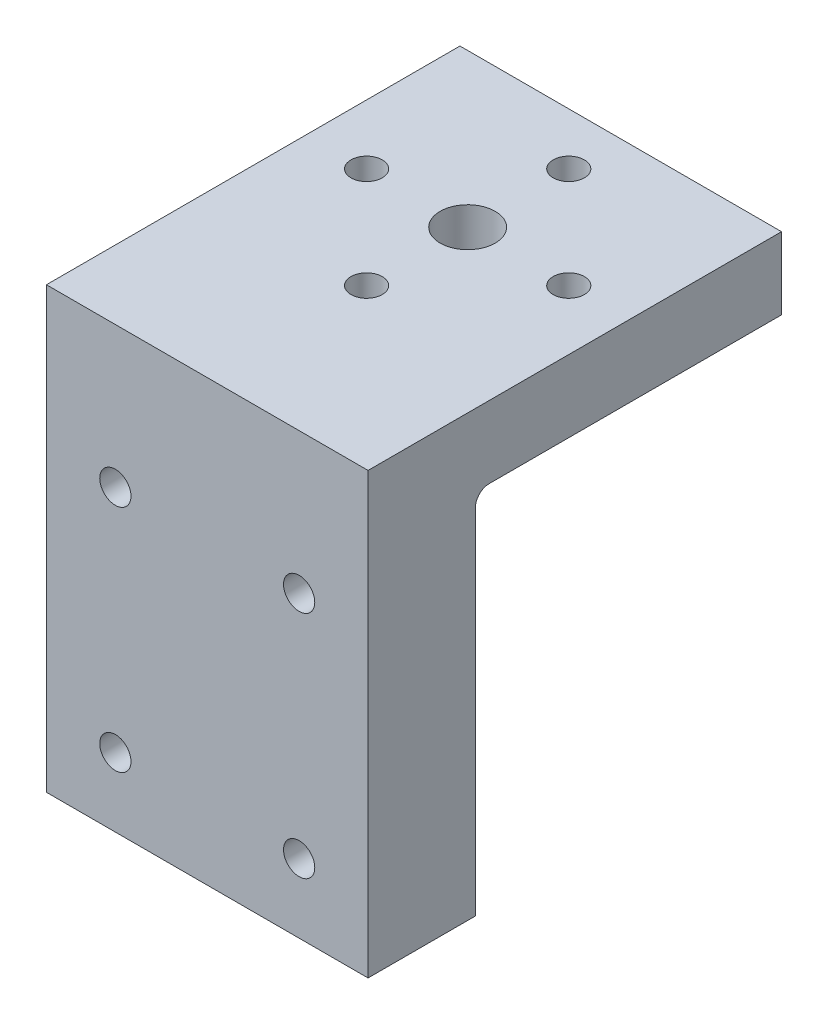
SolidWorks part; units mm, degrees
ref_plane "Front Plane" through (0, 0, 0) normal (0, 0, 1) x (1, 0, 0)
ref_plane "Top Plane" through (0, 0, 0) normal (0, 1, 0) x (1, 0, 0)
ref_plane "Right Plane" through (0, 0, 0) normal (1, 0, 0) x (0, 0, -1)
sketch "Sketch1" plane through (0, 0, 0) normal (0, 1, 0) x (1, 0, 0)
  line L1 (-17.5, -22.5) -> (17.5, -22.5)
  line L2 (-17.5, -22.5) -> (-17.5, 22.5)
  line L3 (-17.5, 22.5) -> (17.5, 22.5)
  line L4 (17.5, -22.5) -> (17.5, 22.5)
  line L5 (-17.5, -22.5) -> (17.5, 22.5) construction
  line L6 (-17.5, 22.5) -> (17.5, -22.5) construction
  point P0 (0, 0)
  dimension "D1" = 45
  dimension "D2" = 35
extrude "Boss-Extrude1" add sketch "Sketch1" against normal blind 7.8384
sketch "Sketch2" plane through (0, -7.8384, 0) normal (0, -1, 0) x (1, 0, 0)
  line L0 (17.5, 22.5) -> (17.5, -22.5) construction
  line L1 (-17.5, 22.5) -> (17.5, 22.5)
  line L2 (-17.5, 22.5) -> (-17.5, 10.8151)
  line L3 (-17.5, 10.8151) -> (17.5, 10.8151)
  line L4 (17.5, 22.5) -> (17.5, 10.8151)
  dimension "D1" = 11.6849
extrude "Boss-Extrude2" add sketch "Sketch2" along normal blind 40
sketch "Sketch3" plane through (0, -7.8384, 0) normal (0, -1, 0) x (1, 0, 0)
  line L1 (-17.5, -5.8424) -> (-22.3083, -5.8424) construction
  line L2 (-17.5, -22.5) -> (-17.5, 10.8151) construction
  circle A0 centre (0, -5.8424) radius 9
  dimension "D1" = 18
extrude "Cut-Extrude1" cut sketch "Sketch3" against normal blind 2
sketch "Sketch4" plane through (0, -7.8384, 0) normal (0, -1, 0) x (1, 0, 0)
  circle A0 centre (0, -5.8424) radius 3
  circle A1 centre (0, -5.8424) radius 9 construction
  circle A2 centre (0, -5.8424) radius 11 construction
  circle A3 centre (0, 5.1576) radius 1.7
  circle A4 centre (11, -5.8424) radius 1.7
  circle A5 centre (0, -16.8424) radius 1.7
  circle A6 centre (-11, -5.8424) radius 1.7
  dimension "D1" = 6
  dimension "D2" = 22
  dimension "D3" = 3.4
  dimension "D4" = 4
extrude "Cut-Extrude2" cut sketch "Sketch4" against normal up to surface (7.8384 mm away) up to face at (0, 0, 0)
sketch "Sketch5" plane through (0, 0, 10.8151) normal (0, 0, -1) x (-1, 0, 0)
  line L0 (17.5, -47.8384) -> (-17.5, -47.8384) construction
  line L1 (-17.5, -47.8384) -> (-17.5, -7.8384) construction
  line L2 (0, -47.8384) -> (0, -51.295) construction
  line L3 (17.5, -27.8384) -> (22.8541, -27.8384) construction
  line L4 (17.5, -47.8384) -> (17.5, -7.8384) construction
  circle A0 centre (-10, -40.3384) radius 1.7
  circle A1 centre (10, -40.3384) radius 1.7
  circle A2 centre (-10, -15.3384) radius 1.7
  circle A3 centre (10, -15.3384) radius 1.7
  dimension "D1" = 3.4
  dimension "D2" = 7.5
  dimension "D3" = 7.5
extrude "Cut-Extrude3" cut sketch "Sketch5" against normal up to surface (11.6849 mm away) up to face at (0, -23.9192, 22.5)
fillet "Fillet1" radius 1.5 1 edges at (0, -7.8384, 10.8151)
equation "\"Force\"= 300"
equation "\"Safety Factor\"= 3"
equation "\"Safety Factor Force\"= \"Force\" * \"Safety Factor\""
equation "\"Shaft Length\"= 18"
equation "\"Base\"= 35"
equation "\"Length1\"= 45"
equation "\"Length2\"= 40"
equation "\"Yield Strength\"= 45.2"
equation "\"Moment1\"= \"Safety Factor Force\" * \"Shaft Length\""
equation "\"Height1\"= SQR ( ( 6 * \"Moment1\" ) / ( \"Base\" * \"Yield Strength\" ) )"
equation "\"Moment2\"= \"Safety Factor Force\" * \"Length2\""
equation "\"Height2\"= SQR ( ( 6 * \"Moment2\" ) / ( \"Base\" * \"Yield Strength\" ) )"
equation "\"D1@Sketch1\"=\"Length1\""
equation "\"D2@Sketch1\"=\"Base\""
equation "\"D1@Boss-Extrude1\"=\"Height1\""
equation "\"D1@Sketch2\"=\"Height2\""
equation "\"D1@Boss-Extrude2\"=\"Length2\""
equation "\"D1@Sketch3\"=\"Shaft Length\""
